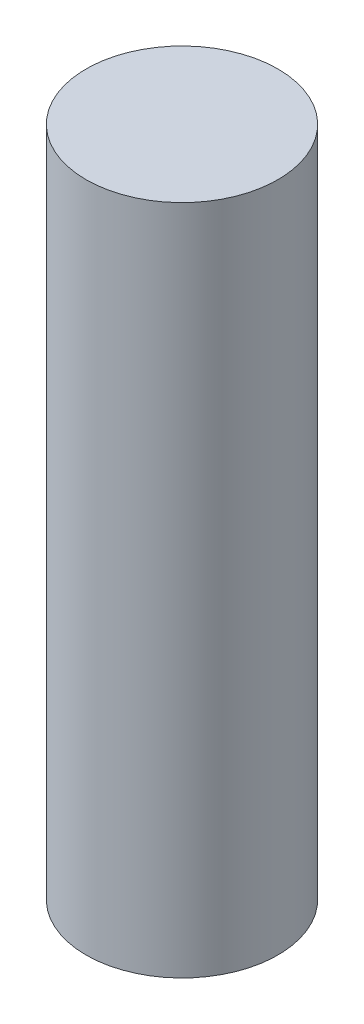
SolidWorks part; units mm, degrees
ref_plane "Front Plane" through (0, 0, 0) normal (0, 0, 1) x (1, 0, 0)
ref_plane "Top Plane" through (0, 0, 0) normal (0, 1, 0) x (1, 0, 0)
ref_plane "Right Plane" through (0, 0, 0) normal (1, 0, 0) x (0, 0, -1)
sketch "Sketch1" plane through (0, 0, 0) normal (0, 1, 0) x (1, 0, 0)
  circle A0 centre (0, 0) radius 3
  dimension "D1" = 6
extrude "Boss-Extrude1" add sketch "Sketch1" along normal blind 21
